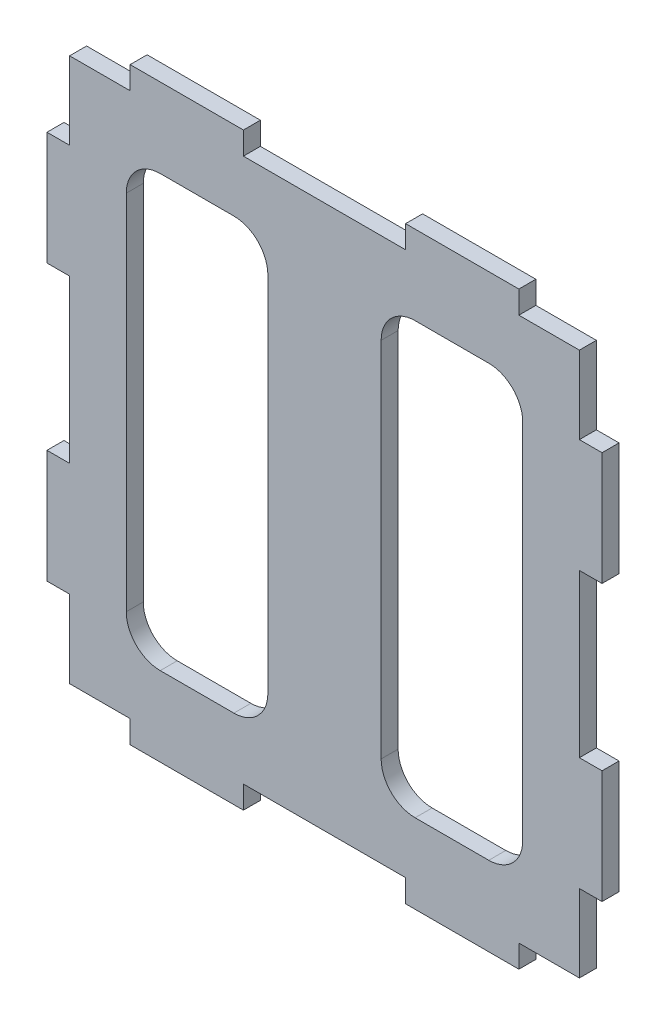
SolidWorks part; units mm, degrees
ref_plane "前视基准面" through (0, 0, 0) normal (0, 0, 1) x (1, 0, 0)
ref_plane "上视基准面" through (0, 0, 0) normal (0, 1, 0) x (1, 0, 0)
ref_plane "右视基准面" through (0, 0, 0) normal (1, 0, 0) x (0, 0, -1)
other "Configuration Table"
sketch "草图1" plane through (0, 0, 0) normal (0, 0, 1) x (1, 0, 0)
  line L0 (1932.0596, 1023.9069) -> (1922.0596, 1023.9069)
  line L1 (1946.376, 1023.9069) -> (1956.376, 1023.9069)
  line L2 (1922.0596, 1021.9069) -> (1916.7178, 1021.9069)
  line L3 (1956.376, 1021.9069) -> (1961.7178, 1021.9069)
  line L4 (1956.376, 1023.9069) -> (1956.376, 1021.9069)
  line L5 (1946.376, 1023.9069) -> (1946.376, 1021.9069)
  line L6 (1946.376, 1021.9069) -> (1932.0596, 1021.9069)
  line L7 (1916.7178, 1005.0651) -> (1916.7178, 990.7487)
  line L8 (1916.7178, 980.7487) -> (1916.7178, 973.9069)
  line L9 (1916.7178, 1015.0651) -> (1916.7178, 1021.9069)
  line L10 (1961.7178, 1005.0651) -> (1961.7178, 990.7487)
  line L11 (1961.7178, 980.7487) -> (1961.7178, 973.9069)
  line L12 (1961.7178, 1015.0651) -> (1961.7178, 1021.9069)
  line L13 (1914.7178, 1015.0651) -> (1916.7178, 1015.0651)
  line L14 (1914.7178, 1005.0651) -> (1916.7178, 1005.0651)
  line L15 (1914.7178, 990.7487) -> (1916.7178, 990.7487)
  line L16 (1914.7178, 980.7487) -> (1916.7178, 980.7487)
  line L17 (1916.7178, 1015.0651) -> (1914.7178, 1015.0651)
  line L18 (1914.7178, 1015.0651) -> (1914.7178, 1005.0651)
  line L19 (1914.7178, 990.7487) -> (1914.7178, 980.7487)
  line L20 (1916.7178, 1021.9069) -> (1922.0596, 1021.9069)
  line L21 (1932.0596, 1021.9069) -> (1939.2178, 1021.9069)
  line L22 (1963.7178, 1015.0651) -> (1961.7178, 1015.0651)
  line L23 (1963.7178, 1005.0651) -> (1961.7178, 1005.0651)
  line L24 (1963.7178, 990.7487) -> (1961.7178, 990.7487)
  line L25 (1963.7178, 980.7487) -> (1961.7178, 980.7487)
  line L26 (1961.7178, 1015.0651) -> (1963.7178, 1015.0651)
  line L27 (1963.7178, 1015.0651) -> (1963.7178, 1005.0651)
  line L28 (1963.7178, 990.7487) -> (1963.7178, 980.7487)
  line L29 (1916.7178, 973.9069) -> (1922.0596, 973.9069)
  line L30 (1932.0596, 973.9069) -> (1946.376, 973.9069)
  line L31 (1956.376, 973.9069) -> (1961.7178, 973.9069)
  line L32 (1932.0596, 1023.9069) -> (1932.0596, 1021.9069)
  line L33 (1922.0596, 1023.9069) -> (1922.0596, 1021.9069)
  line L34 (1956.376, 973.9069) -> (1956.376, 971.9069)
  line L35 (1946.376, 973.9069) -> (1946.376, 971.9069)
  line L36 (1932.0596, 973.9069) -> (1932.0596, 971.9069)
  line L37 (1922.0596, 973.9069) -> (1922.0596, 971.9069)
  line L38 (1922.0596, 971.9069) -> (1932.0596, 971.9069)
  line L39 (1946.376, 971.9069) -> (1956.376, 971.9069)
  line L40 (1921.7178, 1013.9069) -> (1921.7178, 981.9069)
  line L41 (1924.7178, 978.9069) -> (1931.2178, 978.9069)
  line L42 (1924.7178, 1016.9069) -> (1931.2178, 1016.9069)
  line L43 (1956.7178, 1013.9069) -> (1956.7178, 981.9069)
  line L44 (1953.7178, 978.9069) -> (1947.2178, 978.9069)
  line L45 (1953.7178, 1016.9069) -> (1947.2178, 1016.9069)
  line L46 (1934.2178, 1013.9069) -> (1934.2178, 981.9069)
  line L47 (1944.2178, 1013.9069) -> (1944.2178, 981.9069)
  arc A0 (1921.7178, 981.9069) -> (1924.7178, 978.9069) centre (1924.7178, 981.9069) ccw
  arc A1 (1924.7178, 1016.9069) -> (1921.7178, 1013.9069) centre (1924.7178, 1013.9069) ccw
  arc A2 (1953.7178, 978.9069) -> (1956.7178, 981.9069) centre (1953.7178, 981.9069) ccw
  arc A3 (1956.7178, 1013.9069) -> (1953.7178, 1016.9069) centre (1953.7178, 1013.9069) ccw
  arc A4 (1931.2178, 978.9069) -> (1934.2178, 981.9069) centre (1931.2178, 981.9069) ccw
  arc A5 (1934.2178, 1013.9069) -> (1931.2178, 1016.9069) centre (1931.2178, 1013.9069) ccw
  arc A6 (1944.2178, 981.9069) -> (1947.2178, 978.9069) centre (1947.2178, 981.9069) ccw
  arc A7 (1947.2178, 1016.9069) -> (1944.2178, 1013.9069) centre (1947.2178, 1013.9069) ccw
extrude "凸台-拉伸1" add sketch "草图1" along normal blind 1.5 contours L35 L39 L34 L31 L11 L25 L28 L24 L10 L23 L27 L22 L12 L3 L4 L1 L5 L6 L32 L0 L33 L2 L9 L13 L18 L14 L7 L15 L19 L16 L8 L29 L37 L38 L36 L30 A7 L45 A3 L43 A2 L44 A6 L47 A5 L46 A4 L41
